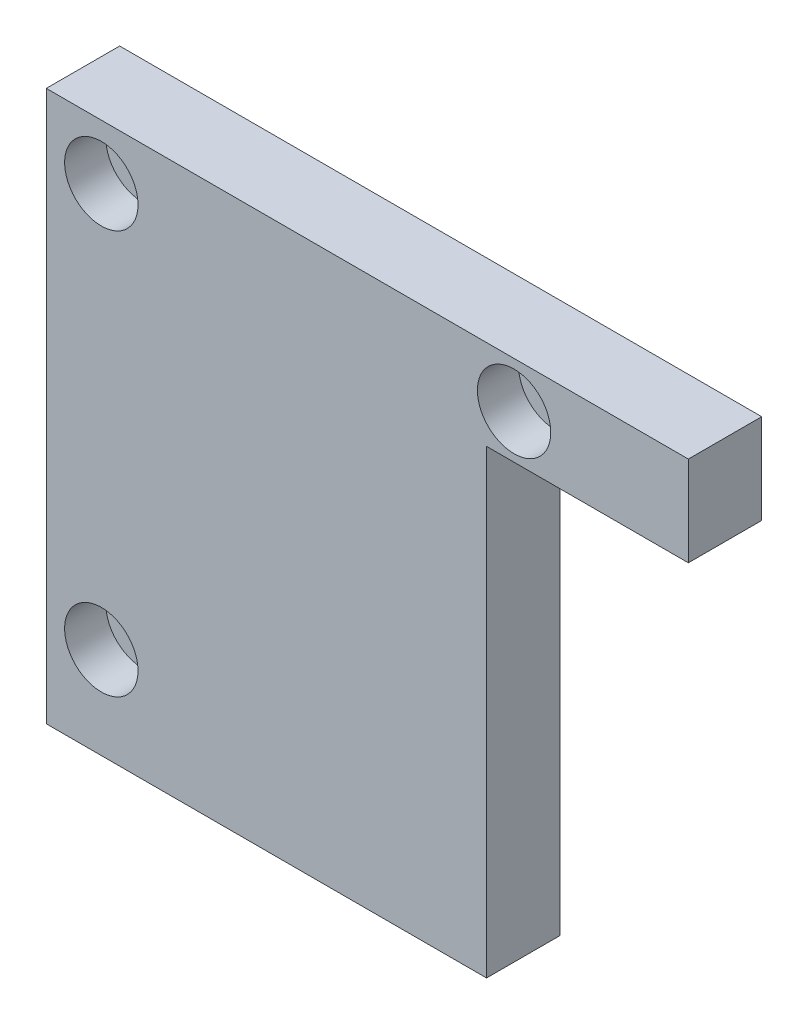
SolidWorks part; units mm, degrees
material "AISI 316 Stainless Steel Sheet (SS)"
ref_plane "Front Plane" through (0, 0, 0) normal (0, 0, 1) x (1, 0, 0)
ref_plane "Top Plane" through (0, 0, 0) normal (0, 1, 0) x (1, 0, 0)
ref_plane "Right Plane" through (0, 0, 0) normal (1, 0, 0) x (0, 0, -1)
sketch "Sketch1" plane through (0, 0, 0) normal (0, 0, 1) x (1, 0, 0)
  line L1 (0, 0) -> (48, 0)
  line L2 (0, 0) -> (0, 60)
  line L3 (0, 60) -> (35, 60)
  line L4 (48, 0) -> (48, 50.2)
  line L5 (0, 60) -> (70, 60)
  line L6 (0, 60) -> (0, 44.485)
  line L7 (48, 50.2) -> (70, 50.2)
  line L8 (70, 60) -> (70, 50.2)
  dimension "D1" = 48
  dimension "D2" = 70
  dimension "D3" = 60
  dimension "D4" = 9.8
extrude "Boss-Extrude1" add sketch "Sketch1" along normal mid plane 8 contours L8 L5 L3 L2 L1 L4 L7
hole_wizard "CBORE for M5 Hex Head Bolt1" positions "Sketch3" profile "Sketch4" counterbore size "M5" standard "ANSI Metric" end condition through all
sketch "Sketch3" plane through (0, 0, 4) normal (0, 0, 1) x (1, 0, 0)
  line L0 (0, 0) -> (0, 60) construction
  line L2 (0, 60) -> (70, 60) construction
  point P0 (6, 10)
  point P2 (6, 54)
  point P15 (51, 55)
  dimension "D1" = 6
  dimension "D2" = 6
  dimension "D3" = 6
  dimension "D4" = 44
  dimension "D5" = 1
  dimension "D6" = 45
sketch "Sketch4" plane through (6, 10, 4) normal (1, 0, 0) x (0, -1, 0)
  line L0 (0, 0) -> (0, 8)
  line L1 (0, 8) -> (2, 8)
  line L3 (2, 8) -> (2, 4.5)
  line L4 (2, 4.5) -> (4, 4.5)
  line L5 (4, 4.5) -> (4, 0)
  line L7 (4, 0) -> (0, 0)
  line L11 (0, -6.35) -> (0, 107.95) construction
  dimension "Thru Hole Dia." = 4
  dimension "Thru Hole Depth" = 8
  dimension "C'Bore Dia." = 8
  dimension "C'Bore Depth" = 4.5
